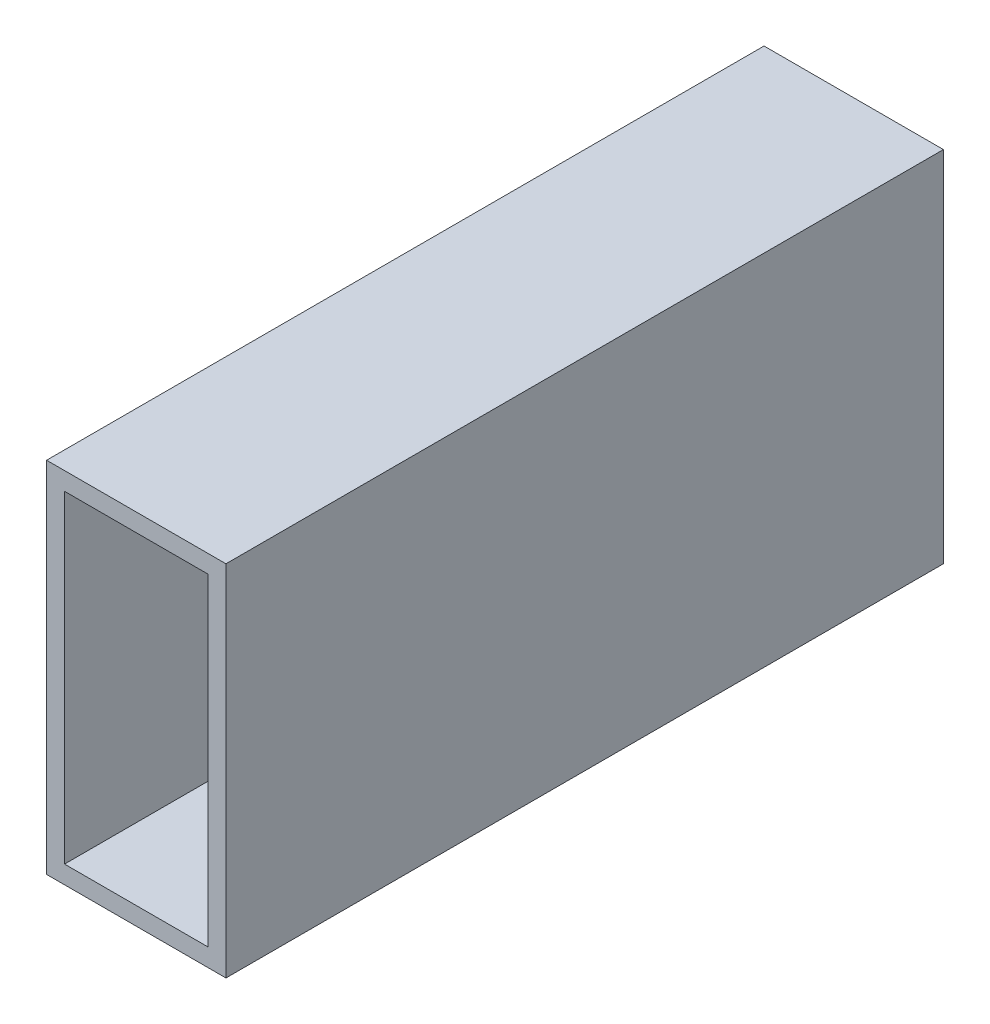
SolidWorks part; units mm, degrees
ref_plane "Front Plane" through (0, 0, 0) normal (0, 0, 1) x (1, 0, 0)
ref_plane "Top Plane" through (0, 0, 0) normal (0, 1, 0) x (1, 0, 0)
ref_plane "Right Plane" through (0, 0, 0) normal (1, 0, 0) x (0, 0, -1)
sketch "Sketch1" plane through (0, 0, 0) normal (0, 0, 1) x (1, 0, 0)
  line L0 (-4, 9) -> (4, 9)
  line L1 (-5, -10) -> (5, -10)
  line L2 (-5, -10) -> (-5, 10)
  line L3 (-5, 10) -> (5, 10)
  line L4 (5, -10) -> (5, 10)
  line L5 (-5, -10) -> (5, 10) construction
  line L6 (-5, 10) -> (5, -10) construction
  line L7 (4, -9) -> (4, 9)
  line L8 (-4, -9) -> (4, -9)
  line L9 (-4, -9) -> (-4, 9)
  point P0 (0, 0)
  dimension "D1" = 10
  dimension "D2" = 20
  dimension "D3" = 1
extrude "Boss-Extrude1" add sketch "Sketch1" along normal blind 40
